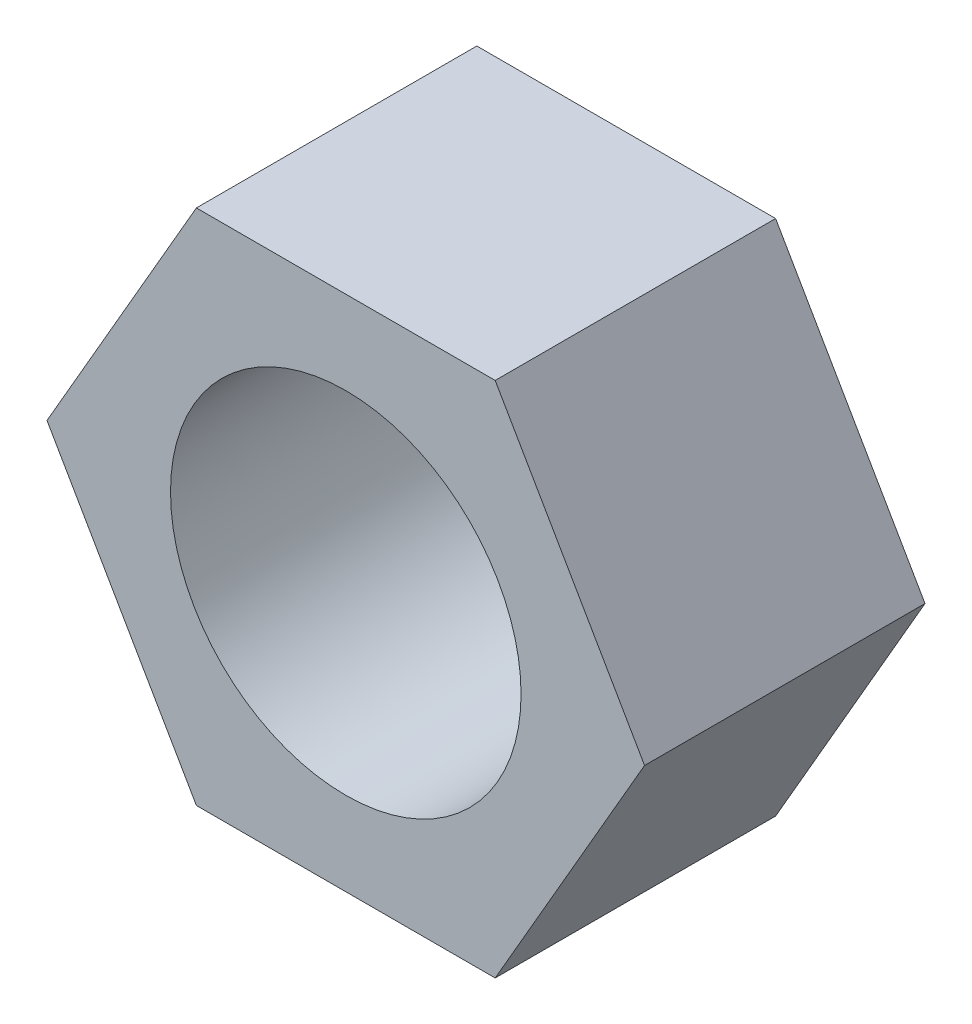
SolidWorks part; units mm, degrees
ref_plane "Front Plane" through (0, 0, 0) normal (0, 0, 1) x (1, 0, 0)
ref_plane "Top Plane" through (0, 0, 0) normal (0, 1, 0) x (1, 0, 0)
ref_plane "Right Plane" through (0, 0, 0) normal (1, 0, 0) x (0, 0, -1)
sketch "Sketch1" plane through (0, 0, 0) normal (0, 0, 1) x (1, 0, 0)
  line L1 (-73.5199, 77.7817) -> (-75.6508, 81.4726)
  line L2 (-75.6508, 81.4726) -> (-79.9127, 81.4726)
  line L3 (-79.9127, 81.4726) -> (-82.0436, 77.7817)
  line L4 (-82.0436, 77.7817) -> (-79.9127, 74.0909)
  line L5 (-79.9127, 74.0909) -> (-75.6508, 74.0909)
  line L6 (-75.6508, 74.0909) -> (-73.5199, 77.7817)
  circle A0 centre (-77.7817, 77.7817) radius 2.5
  circle A1 centre (-77.7817, 77.7817) radius 3.6909 construction
extrude "Boss-Extrude1" add sketch "Sketch1" along normal blind 4
